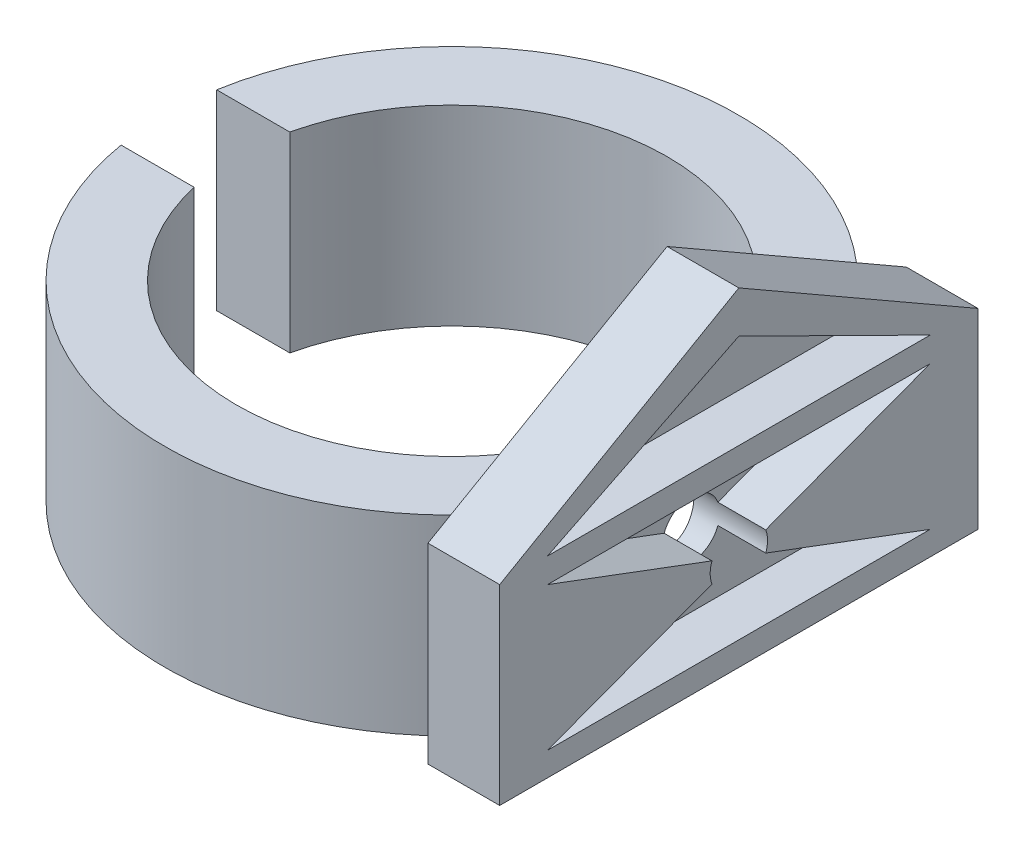
SolidWorks part; units mm, degrees
ref_plane "Front Plane" through (0, 0, 0) normal (0, 0, 1) x (1, 0, 0)
ref_plane "Top Plane" through (0, 0, 0) normal (0, 1, 0) x (1, 0, 0)
ref_plane "Right Plane" through (0, 0, 0) normal (1, 0, 0) x (0, 0, -1)
sketch "Sketch1" plane through (0, 0, 0) normal (0, 1, 0) x (1, 0, 0)
  circle A0 centre (0, 0) radius 22.5
  circle A1 centre (0, 0) radius 30
  dimension "D1" = 45
  dimension "D2" = 60
extrude "Boss-Extrude1" add sketch "Sketch1" along normal blind 20
ref_plane "Plane1" through (22.5, 0, 0) normal (1, 0, 0) x (0, 0, -1)
sketch "Sketch2" plane through (22.5, 0, 0) normal (1, 0, 0) x (0, 0, -1)
  line L1 (-25, 20) -> (25, 20)
  line L2 (-25, 20) -> (-25, 0)
  line L3 (-25, 0) -> (25, 0)
  line L4 (25, 20) -> (25, 0)
  line L5 (-25, 20) -> (25, 0) construction
  line L6 (-25, 0) -> (25, 20) construction
  point P0 (0, 10)
  point P5 (0, 0)
  dimension "D1" = 20
  dimension "D2" = 50
extrude "Boss-Extrude2" add sketch "Sketch2" along normal blind 7.5
ref_plane "Plane2" through (0, 0, 0) normal (0, 1, 0) x (1, 0, 0)
sketch "Sketch4" plane through (0, 0, 0) normal (0, 1, 0) x (1, 0, 0)
  line L0 (-60, 0) -> (0, 0) construction
  line L1 (0, 0) -> (0, 30) construction
  line L2 (0, 0) -> (0, -30) construction
  line L4 (-33.9902, 5) -> (-19.5916, 5)
  line L5 (-33.9902, 5) -> (-33.9902, -5)
  line L6 (-33.9902, -5) -> (-19.5916, -5)
  line L7 (-19.5916, 5) -> (-19.5916, -5)
  line L8 (-33.9902, 5) -> (-19.5916, -5) construction
  line L9 (-33.9902, -5) -> (-19.5916, 5) construction
  point P3 (-26.7909, 0)
  dimension "D1" = 5
  dimension "D2" = 5
extrude "Cut-Extrude1" cut sketch "Sketch4" along normal blind 20
ref_plane "Plane3" through (30, 0, 0) normal (1, 0, 0) x (0, 0, -1)
sketch "Sketch7" plane through (30, 0, 0) normal (1, 0, 0) x (0, 0, -1)
  line L0 (-1, 9.625) -> (-20, 2.5)
  line L1 (20, 2.5) -> (-20, 2.5)
  line L2 (20, 2.5) -> (20, 17.5) construction
  line L3 (20, 17.5) -> (-20, 17.5)
  line L4 (-20, 2.5) -> (-20, 17.5) construction
  line L5 (20, 2.5) -> (1, 9.625)
  line L6 (20, 17.5) -> (1, 10.375)
  line L8 (1, 10.375) -> (1, 9.625)
  line L10 (-1, 10.375) -> (-1, 9.625)
  line L13 (-1, 10.375) -> (-20, 17.5)
  point P0 (0, 10)
  point P5 (0, 0)
  point P6 (0, 10)
  point P11 (0, 0)
  point P12 (0, 0)
  point P13 (0, 0)
extrude "Cut-Extrude3" cut sketch "Sketch7" against normal blind 5
sketch "Sketch8" plane through (30, 0, 0) normal (1, 0, 0) x (0, 0, -1)
  circle A0 centre (0, 10) radius 3
extrude "Cut-Extrude4" cut sketch "Sketch8" against normal blind 10
sketch "Sketch9" plane through (30, 0, 0) normal (1, 0, 0) x (0, 0, -1)
  line L0 (-25, 20) -> (0, 34.3578)
  line L1 (25, 20) -> (0, 34.3578)
  line L2 (0, 10) -> (0, 46.3805) construction
  line L3 (-25, 20) -> (25, 20)
extrude "Boss-Extrude3" add sketch "Sketch9" against normal blind 7.5
sketch "Sketch10" plane through (30, 0, 0) normal (1, 0, 0) x (0, 0, -1)
  line L0 (-20, 20.0884) -> (20, 20.0884)
  line L1 (20, 20.0884) -> (0, 29.991)
  line L2 (0, 29.991) -> (-20, 20.0884)
  point P3 (-19.1272, 20.0884)
  dimension "D1" = 40
  dimension "D2" = 0
extrude "Cut-Extrude5" cut sketch "Sketch10" against normal blind 5
